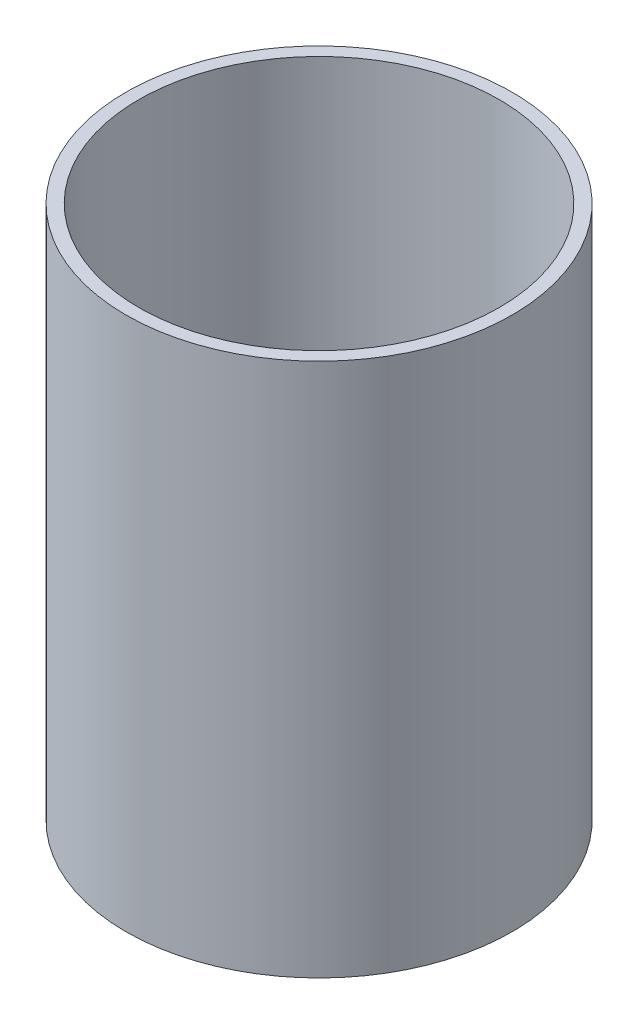
SolidWorks part; units mm, degrees
ref_plane "前视基准面" through (0, 0, 0) normal (0, 0, 1) x (1, 0, 0)
ref_plane "上视基准面" through (0, 0, 0) normal (0, 1, 0) x (1, 0, 0)
ref_plane "右视基准面" through (0, 0, 0) normal (1, 0, 0) x (0, 0, -1)
other "Configuration Table"
sketch "草图1" plane through (0, 0, 0) normal (0, 1, 0) x (1, 0, 0)
  circle A0 centre (0, 0) radius 30
extrude "凸台-拉伸1" add sketch "草图1" along normal blind 3
sketch "草图2" plane through (0, 3, 0) normal (0, 1, 0) x (1, 0, 0)
  circle A0 centre (0, 0) radius 30
extrude "拉伸-薄壁1" add sketch "草图2" along normal blind 80 thin thin type one direction reverse wall 2
